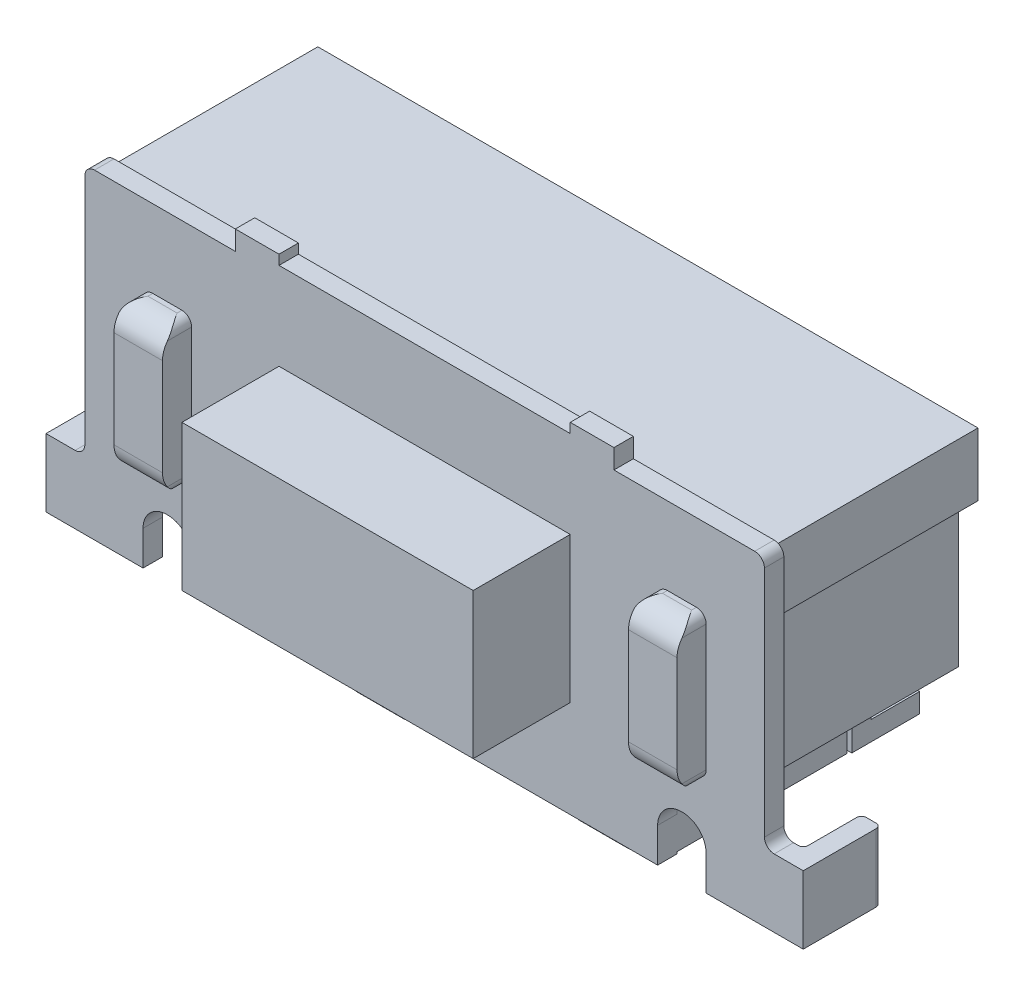
SolidWorks part; units mm, degrees
ref_plane "Alzado" through (0, 0, 0) normal (0, 0, 1) x (1, 0, 0)
ref_plane "Planta" through (0, 0, 0) normal (0, 1, 0) x (1, 0, 0)
ref_plane "Vista lateral" through (0, 0, 0) normal (1, 0, 0) x (0, 0, -1)
sketch "Croquis2" plane through (0, 0, 0) normal (0, 0, 1) x (1, 0, 0)
  line L0 (0, 0) -> (7.8, 0)
  line L1 (7.8, 0) -> (7.8, 3.5)
  line L2 (7.8, 3.5) -> (0, 3.5)
  line L3 (0, 3.5) -> (0, 0)
  dimension "D1" = 3.5
  dimension "D2" = 7.8
extrude "Saliente-Extruir1" add sketch "Croquis2" along normal blind 2.5
sketch "Croquis3" plane through (0, 0, 2.5) normal (0, 0, 1) x (1, 0, 0)
  line L0 (2.4, 2.5) -> (5.4, 2.5)
  line L5 (5.4, 1) -> (2.4, 1)
  line L6 (5.4, 2.5) -> (5.4, 1)
  line L8 (2.4, 1) -> (2.4, 2.5)
  dimension "D1" = 3
  dimension "D3" = 1.5
extrude "Saliente-Extruir2" add sketch "Croquis3" along normal blind 1
sketch "Croquis4" plane through (0, 0, 0) normal (0, -1, 0) x (1, 0, 0)
  line L0 (3.9, 2.5) -> (3.9, 1.5) construction
  line L1 (2.4, 2.5) -> (5.4, 2.5) construction
  line L6 (2.75, 1.5) -> (5.05, 1.5) construction
  circle A0 centre (5.05, 1.5) radius 0.4
  circle A1 centre (2.75, 1.5) radius 0.4
  dimension "D3" = 0.8
  dimension "D5" = 0.8
  dimension "D1" = 1
  dimension "D2" = 1.15
  dimension "D4" = 1.15
  dimension "D6" = 2.3
extrude "Saliente-Extruir3" add sketch "Croquis4" along normal blind 0.75
sketch "Croquis5" plane through (0, 0, 2.5) normal (0, 0, 1) x (1, 0, 0)
  line L0 (3.9, 3.5) -> (0.4, 3.5) construction
  line L1 (7.8, 3.5) -> (0, 3.5) construction
  line L2 (0.4, 3.5) -> (7.4, 3.5) construction
  line L3 (0.4, 0) -> (0.4, 0.7) construction
  line L4 (0, 0) -> (7.8, 0) construction
  line L5 (7.4, 0) -> (7.4, 0.7) construction
  line L9 (7.4, 3.5) -> (7.4, 0.7)
  line L10 (7.4, 0.7) -> (7.8, 0.7)
  line L11 (7.8, 0) -> (7.8, 3.5) construction
  line L12 (7.8, 0.7) -> (7.8, 3.5)
  line L13 (7.8, 3.5) -> (7.4, 3.5)
  line L16 (0.4, 3.5) -> (0.4, 0.7)
  line L17 (0.4, 0.7) -> (0, 0.7)
  line L18 (0, 3.5) -> (0, 0) construction
  line L19 (0, 0.7) -> (0, 3.5)
  line L20 (0, 3.5) -> (0.4, 3.5)
  dimension "D1" = 3.5
  dimension "D2" = 7
  dimension "D3" = 0.7
extrude "Cortar-Extruir1" cut sketch "Croquis5" against normal blind 2.5
sketch "Croquis6" plane through (0, 0, 2.5) normal (0, 0, 1) x (1, 0, 0)
  line L0 (0.2, 0.7) -> (0.3, 0.7)
  line L1 (0, 0.7) -> (0.4, 0.7) construction
  line L2 (0.4, 0.8) -> (0.4, 0.9)
  line L3 (0.4, 0.7) -> (0.4, 3.5) construction
  line L4 (0.2, 0.7) -> (0.4, 0.7)
  line L5 (0.4, 0.7) -> (0.4, 0.9)
  arc A0 (0.4, 0.8) -> (0.3, 0.7) centre (0.3, 0.8) cw
  point P10 (0.4, 0.7)
  line M3 (0.4, 3.5) -> (0.4, 0.7)
  line M4 (0.4, 0.7) -> (0, 0.7)
  dimension "D3" = 0.1
  dimension "D1" = 0.2
  dimension "D2" = 0.2
extrude "Saliente-Extruir4" add sketch "Croquis6" against normal blind 2.5 contours A0 M3 M4
sketch "Croquis7" plane through (0, 0, 2.5) normal (0, 0, 1) x (1, 0, 0)
  line L0 (7.6, 0.7) -> (7.5, 0.7)
  line L1 (7.4, 0.7) -> (7.8, 0.7) construction
  line L2 (7.4, 0.8) -> (7.4, 0.9)
  line L3 (7.4, 3.5) -> (7.4, 0.7) construction
  line L4 (7.4, 0.9) -> (7.4, 0.7)
  line L5 (7.4, 0.7) -> (7.6, 0.7)
  arc A0 (7.5, 0.7) -> (7.4, 0.8) centre (7.5, 0.8) cw
  point P10 (7.4, 0.7)
  line M12 (7.8, 0.7) -> (7.4, 0.7)
  line M13 (7.4, 0.7) -> (7.4, 3.5)
  dimension "D2" = 0.1
  dimension "D1" = 0.2
extrude "Saliente-Extruir5" add sketch "Croquis7" against normal blind 2.5 contours A0 M12 M13
sketch "Croquis8" plane through (0, 0, 2.5) normal (0, 0, 1) x (1, 0, 0)
  line L0 (7.8, 0) -> (7.8, 3.5) construction
  line L1 (3.9, 0) -> (6.3, 0) construction
  line L2 (0, 0) -> (7.8, 0) construction
  line L3 (6.3, 0) -> (6.3, 1) construction
  line L4 (6.3, 1.1) -> (6.3, 2.4)
  line L5 (6.4, 2.5) -> (6.7, 2.5)
  line L6 (6.4, 1) -> (6.7, 1)
  line L7 (6.8, 1.1) -> (6.8, 2.4)
  line L8 (3.9, 0) -> (1.5, 0) construction
  line L9 (1.5, 0) -> (1.5, 1) construction
  line L10 (1.5, 1.1) -> (1.5, 2.4)
  line L11 (1.4, 2.5) -> (1.1, 2.5)
  line L12 (1, 2.4) -> (1, 1.1)
  line L13 (1.1, 1) -> (1.4, 1)
  arc A0 (6.7, 1) -> (6.8, 1.1) centre (6.7, 1.1) ccw
  arc A1 (6.4, 1) -> (6.3, 1.1) centre (6.4, 1.1) cw
  arc A2 (6.3, 2.4) -> (6.4, 2.5) centre (6.4, 2.4) cw
  arc A3 (6.7, 2.5) -> (6.8, 2.4) centre (6.7, 2.4) cw
  arc A4 (1.4, 1) -> (1.5, 1.1) centre (1.4, 1.1) ccw
  arc A5 (1.5, 2.4) -> (1.4, 2.5) centre (1.4, 2.4) ccw
  arc A6 (1.1, 2.5) -> (1, 2.4) centre (1.1, 2.4) ccw
  arc A7 (1, 1.1) -> (1.1, 1) centre (1.1, 1.1) ccw
  point P23 (6.3, 2.5)
  point P26 (6.8, 2.5)
  point P32 (1.5, 2.5)
  point P35 (1, 2.5)
  dimension "D5" = 0.1
  dimension "D6" = 0.1
  dimension "D7" = 0.1
  dimension "D8" = 0.1
  dimension "D9" = 0.1
  dimension "D10" = 0.1
  dimension "D11" = 0.1
  dimension "D12" = 0.1
  dimension "D1" = 2.4
  dimension "D2" = 0.5
  dimension "D3" = 2.4
  dimension "D4" = 0.5
extrude "Saliente-Extruir6" add sketch "Croquis8" along normal blind 0.3
sketch "Croquis9" plane through (0, 0, 2.5) normal (0, 0, 1) x (1, 0, 0)
  line L2 (3.9, 3.4) -> (5.4, 3.4)
  line L5 (7.4, 3.5) -> (0.4, 3.5) construction
  line L6 (2.4, 3.5) -> (2.4, 3.4)
  line L7 (5.4, 3.4) -> (5.4, 3.5)
  line L10 (2.4, 3.5) -> (1.95, 3.5)
  line L11 (1.95, 3.5) -> (1.95, 3.3)
  line L12 (1.95, 3.3) -> (0.5, 3.3)
  line L13 (1.95, 3.5) -> (0.4, 3.5)
  line L14 (0.4, 3.5) -> (0.4, 3.2)
  line L15 (2.4, 3.4) -> (3.9, 3.4)
  line L16 (5.4, 3.5) -> (5.85, 3.5)
  line L17 (5.85, 3.5) -> (5.85, 3.3)
  line L18 (5.85, 3.3) -> (7.3, 3.3)
  line L19 (7.4, 3.5) -> (7.4, 0.8) construction
  line L20 (7.4, 3.2) -> (7.4, 2.15)
  line L21 (2.4, 3.5) -> (5.4, 3.5)
  line L22 (5.85, 3.5) -> (7.4, 3.5)
  line L23 (7.4, 3.5) -> (7.4, 3.2)
  arc A0 (0.5, 3.3) -> (0.4, 3.2) centre (0.5, 3.2) ccw
  arc A1 (7.3, 3.3) -> (7.4, 3.2) centre (7.3, 3.2) cw
  point P18 (7.4, 3.3)
  line M15 (7.4, 0.8) -> (7.4, 3.5)
  line M16 (7.4, 3.5) -> (0.4, 3.5)
  line M17 (0.4, 3.5) -> (0.4, 0.8)
  dimension "D3" = 0.1
  dimension "D8" = 0.1
  dimension "D1" = 0.1
  dimension "D2" = 0.2
  dimension "D4" = 1.5
  dimension "D5" = 1.5
  dimension "D6" = 0.45
  dimension "D7" = 0.45
extrude "Cortar-Extruir2" cut sketch "Croquis9" against normal blind 2.5 contours A0 L12 L11 M16 M17 | L6 L15 L2 L7 M16 | L18 A1 L17 M15 M16
sketch "Croquis10" plane through (0, 0, 0) normal (0, -1, 0) x (1, 0, 0)
  line L0 (3.9, 2.5) -> (3.9, 2.3) construction
  line L1 (0, 2.5) -> (7.8, 2.5) construction
  line L2 (0.2, 2.25) -> (0.2, 1.75)
  line L4 (0.15, 1.7) -> (0.05, 1.7)
  line L5 (7.8, 2.5) -> (7.8, 0) construction
  line L6 (0.25, 2.3) -> (7.55, 2.3)
  line L7 (7.8, 2.45) -> (7.8, 1.75)
  line L8 (7.6, 2.25) -> (7.6, 1.75)
  line L9 (7.65, 1.7) -> (7.75, 1.7)
  line L10 (0, 2.5) -> (0, 0) construction
  line L11 (0, 1.75) -> (0, 2.45)
  line L12 (0.05, 2.5) -> (7.75, 2.5)
  line L13 (7.8, 1.75) -> (7.8, 0)
  line L14 (7.8, 0) -> (0, 0)
  line L15 (0, 0) -> (0, 1.75)
  arc A0 (0, 2.45) -> (0.05, 2.5) centre (0.05, 2.45) cw
  arc A1 (0.25, 2.3) -> (0.2, 2.25) centre (0.25, 2.25) ccw
  arc A2 (0.05, 1.7) -> (0, 1.75) centre (0.05, 1.75) cw
  arc A3 (0.2, 1.75) -> (0.15, 1.7) centre (0.15, 1.75) cw
  arc A4 (7.55, 2.3) -> (7.6, 2.25) centre (7.55, 2.25) cw
  arc A5 (7.8, 2.45) -> (7.75, 2.5) centre (7.75, 2.45) ccw
  arc A6 (7.8, 1.75) -> (7.75, 1.7) centre (7.75, 1.75) cw
  arc A7 (7.6, 1.75) -> (7.65, 1.7) centre (7.65, 1.75) ccw
  point P21 (0, 2.5)
  point P27 (0, 1.7)
  point P34 (7.8, 2.5)
  point P37 (7.8, 1.7)
  circle M20 centre (2.75, 1.5) radius 0.4
  circle M21 centre (5.05, 1.5) radius 0.4
  line M22 (0, 0) -> (7.8, 0)
  line M23 (7.8, 0) -> (7.8, 2.5)
  line M25 (0, 2.5) -> (0, 0)
  dimension "D2" = 0.05
  dimension "D3" = 0.05
  dimension "D5" = 0.05
  dimension "D6" = 0.05
  dimension "D7" = 0.05
  dimension "D8" = 0.05
  dimension "D9" = 0.05
  dimension "D10" = 0.05
  dimension "D1" = 0.2
  dimension "D4" = 0.8
extrude "Cortar-Extruir3" cut sketch "Croquis10" against normal blind 0.02 contours A7 L8 A4 L6 A1 L2 A3 L4 A2 A6 L9 M25 M22 M23 M21 M20
sketch "Croquis12" plane through (0, 3.3, 0) normal (0, 1, 0) x (1, 0, 0)
  line L0 (7.3, -2.5) -> (7.75, -2.5)
  line L1 (7.8, -2.45) -> (7.8, -1.75)
  line L2 (7.8, 0) -> (7.8, -2.5) construction
  line L3 (7.3, -2.5) -> (7.3, -2.3)
  line L4 (7.3, 0) -> (7.3, -2.5) construction
  line L5 (7.75, -1.7) -> (7.65, -1.7)
  line L6 (7.6, -1.75) -> (7.6, -2.25)
  line L7 (7.55, -2.3) -> (7.3, -2.3)
  line L8 (7.3, -2.3) -> (7.3, 0)
  line L9 (7.3, 0) -> (7.8, 0)
  line L10 (7.8, 0) -> (7.8, -1.75)
  line L11 (0.5, -2.5) -> (0.5, -2.3)
  line L12 (0.5, 0) -> (0.5, -2.5) construction
  line L13 (0.5, -2.5) -> (0.05, -2.5)
  line L14 (0, 0) -> (0, -2.5) construction
  line L15 (0, -2.45) -> (0, -1.75)
  line L16 (0.5, -2.3) -> (0.25, -2.3)
  line L17 (0.2, -2.25) -> (0.2, -1.75)
  line L18 (0.15, -1.7) -> (0.05, -1.7)
  line L19 (0.5, -2.3) -> (0.5, 0)
  line L20 (0.5, 0) -> (0, 0)
  line L21 (0, 0) -> (0, -1.75)
  arc A0 (7.65, -1.7) -> (7.6, -1.75) centre (7.65, -1.75) ccw
  arc A1 (7.8, -1.75) -> (7.75, -1.7) centre (7.75, -1.75) ccw
  arc A2 (7.6, -2.25) -> (7.55, -2.3) centre (7.55, -2.25) cw
  arc A3 (7.75, -2.5) -> (7.8, -2.45) centre (7.75, -2.45) ccw
  arc A4 (0.25, -2.3) -> (0.2, -2.25) centre (0.25, -2.25) cw
  arc A5 (0, -2.45) -> (0.05, -2.5) centre (0.05, -2.45) ccw
  arc A6 (0, -1.75) -> (0.05, -1.7) centre (0.05, -1.75) cw
  arc A7 (0.2, -1.75) -> (0.15, -1.7) centre (0.15, -1.75) ccw
  point P15 (7.6, -1.7)
  point P19 (7.8, -1.7)
  point P24 (7.8, -2.5)
  point P46 (0, -2.5)
  point P49 (0, -1.7)
  line M5 (7.3, -2.5) -> (7.3, 0)
  dimension "D4" = 0.05
  dimension "D5" = 0.05
  dimension "D6" = 0.05
  dimension "D7" = 0.05
  dimension "D8" = 0.05
  dimension "D9" = 0.05
  dimension "D11" = 0.05
  dimension "D12" = 0.05
  dimension "D1" = 0.2
  dimension "D2" = 0.8
  dimension "D3" = 0.2
  dimension "D10" = 0.8
extrude "Cortar-Extruir4" cut sketch "Croquis12" against normal blind 3.3 contours A2 L6 A0 L5 A1 L10 L9 L7 M5 | A7 L17 A4 L16 L19 L20 L21 A6 L18
sketch "Croquis13" plane through (0, 3.5, 0) normal (0, 1, 0) x (1, 0, 0)
  line L0 (0.5, -2.5) -> (0.5, -2.3)
  line L1 (0.5, -2.3) -> (7.3, -2.3)
  line L2 (7.3, -2.3) -> (7.3, -2.5)
  line L3 (7.3, -2.5) -> (0.5, -2.5)
  line L4 (7.3, -2.3) -> (7.3, 0)
  line L5 (7.3, 0) -> (0.5, 0)
  line L6 (0.5, 0) -> (0.5, -2.3)
  line M1 (5.85, 0) -> (5.4, 0)
  line M2 (5.4, 0) -> (5.4, -2.5)
  line M4 (5.85, -2.5) -> (5.85, 0)
extrude "Cortar-Extruir5" cut sketch "Croquis13" against normal blind 0.25 contours L5 L6 L1 M2 | L4 L5 L1 M4 | L1 M2 M4 M1
sketch "Croquis17" plane through (0, 0.02, 0) normal (0, -1, 0) x (1, 0, 0)
  line L0 (3.9, 0) -> (3.9, -0.5889) construction
  line L2 (3.9, 0) -> (6, 0) construction
  line L3 (0.5, 0) -> (7.3, 0) construction
  line L4 (3.9, 0) -> (2.1, 0) construction
  line L5 (6, 0) -> (6.3, 0) construction
  line L6 (6.3, -0.2) -> (6.3, 0.5)
  line L7 (3.9, 2.5) -> (3.9, -0.2) construction
  line L8 (0, 2.5) -> (7.8, 2.5) construction
  line L9 (3.9, -0.2) -> (6.3, -0.2) construction
  line L10 (6.3, 0.5) -> (5.7, 0.5)
  line L11 (5.7, 0.5) -> (5.7, -0.2)
  line L12 (5.7, -0.2) -> (6.3, -0.2)
  line L13 (3.9, -0.5889) -> (1.8, -0.5889) construction
  line L14 (2.1, -0.2) -> (1.5, -0.2)
  line L15 (1.5, -0.2) -> (1.5, 0.5)
  line L16 (1.5, 0.5) -> (2.1, 0.5)
  line L17 (2.1, 0.5) -> (2.1, -0.2)
  point P18 (1.8, 0)
  dimension "D1" = 2.1
  dimension "D2" = 2.1
  dimension "D3" = 0.3
  dimension "D4" = 2.7
  dimension "D5" = 0.7
  dimension "D6" = 0.6
  dimension "D7" = 0.6
  dimension "D8" = 0.7
extrude "Saliente-Extruir7" add sketch "Croquis17" along normal blind 0.02
sketch "Croquis18" plane through (0, 0.02, 0) normal (0, 1, 0) x (1, 0, 0)
  line L0 (1.5, 0.2) -> (2.1, 0.2)
  line L1 (2.1, 0.2) -> (2.1, 0)
  line L2 (2.1, 0) -> (1.5, 0)
  line L3 (1.5, 0) -> (1.5, 0.2)
  line L4 (5.7, 0.2) -> (6.3, 0.2)
  line L5 (6.3, 0.2) -> (6.3, 0)
  line L6 (6.3, 0) -> (5.7, 0)
  line L7 (5.7, 0) -> (5.7, 0.2)
extrude "Saliente-Extruir8" add sketch "Croquis18" along normal blind 0.8
sketch "Croquis19" plane through (0, 0, -0.2) normal (0, 0, -1) x (-1, 0, 0)
  line L0 (-6.3, 0) -> (-5.7, 0)
  line L1 (-1.5, 0) -> (-1.5, 0.2)
  line L2 (-5.7, 0.82) -> (-5.7, 0.02) construction
  line L3 (-5.7, 0.2) -> (-6.3, 0.2)
  line L4 (-6.3, 0.82) -> (-6.3, 0.02) construction
  line L5 (-6.3, 0.2) -> (-6.3, 0.82)
  line L6 (-5.7, 0.2) -> (-5.7, 0.82)
  line L7 (-5.7, 0.82) -> (-6.3, 0.82) construction
  line L8 (-6.3, 0.82) -> (-5.7, 0.82) construction
  line L9 (-5.7, 0.82) -> (-6.3, 0.82)
  line L10 (-1.5, 0) -> (-1.5, 0.82) construction
  line L11 (-1.5, 0.2) -> (-2.1, 0.2)
  line L12 (-2.1, 0.82) -> (-2.1, 0.02) construction
  line L13 (-2.1, 0.2) -> (-2.1, 0.82)
  line L14 (-2.1, 0.82) -> (-1.5, 0.82)
  line L15 (-1.5, 0.82) -> (-1.5, 0.2)
  line M3 (-5.7, 0) -> (-5.7, 0.82)
  line M4 (-5.7, 0.82) -> (-6.3, 0.82)
  line M5 (-6.3, 0.82) -> (-6.3, 0)
  dimension "D1" = 0.2
  dimension "D2" = 0.2
extrude "Cortar-Extruir8" cut sketch "Croquis19" against normal blind 0.5 contours L3 M3 M4 M5 | L15 L14 L13 L11
sketch "Croquis20" plane through (0, 0, 0) normal (0, -1, 0) x (1, 0, 0)
  line L0 (1.5, 0.5) -> (2.1, 0.5)
  line L1 (2.1, 0.5) -> (2.1, 0.55)
  line L2 (2.1, 0.55) -> (1.5, 0.55)
  line L3 (1.5, 0.55) -> (1.5, 0.5)
  line L4 (5.7, 0.5) -> (5.7, 0.55)
  line L5 (5.7, 0.55) -> (6.3, 0.55)
  line L6 (6.3, 0.55) -> (6.3, 0.5)
  line L7 (6.3, 0.5) -> (5.7, 0.5)
  dimension "D1" = 0.05
extrude "Cortar-Extruir9" cut sketch "Croquis20" against normal blind 0.8 contours L3 L0 L1 L2 | L7 L4 L5 L6
sketch "Croquis21" plane through (0, 0.02, 0) normal (0, -1, 0) x (1, 0, 0)
  line L0 (1.5, 0) -> (0.9, 0)
  line L1 (0.5, 0) -> (1.5, 0) construction
  line L2 (1.5, 0) -> (1.5, 2.3)
  line L3 (0.5, 2.3) -> (7.3, 2.3) construction
  line L4 (0.9, 0) -> (0.9, 2.3)
  line L5 (0.25, 2.3) -> (7.55, 2.3) construction
  line L6 (0.9, 2.3) -> (1.5, 2.3)
  line L7 (6.3, 0) -> (6.9, 0)
  line L8 (6.3, 0) -> (7.3, 0) construction
  line L9 (6.3, 0) -> (6.3, 2.3)
  line L10 (6.3, 2.3) -> (6.9, 2.3)
  line L11 (6.9, 2.3) -> (6.9, 0)
  dimension "D1" = 0.6
  dimension "D2" = 0.6
extrude "Cortar-Extruir10" cut sketch "Croquis21" against normal blind 0.8
sketch "Croquis22" plane through (0, 0.02, 0) normal (0, -1, 0) x (1, 0, 0)
  line L0 (0.9, 0) -> (0.9, 2.3)
  line L1 (0.9, 2.3) -> (0.5, 2.3)
  line L2 (0.5, 2.3) -> (0.5, 0)
  line L3 (0.5, 0) -> (0.9, 0)
  line L4 (6.9, 2.3) -> (7.3, 2.3)
  line L5 (7.3, 2.3) -> (7.3, 0)
  line L6 (7.3, 0) -> (6.9, 0)
  line L7 (6.9, 0) -> (6.9, 2.3)
extrude "Cortar-Extruir11" cut sketch "Croquis22" against normal blind 2.58
sketch "Croquis23" plane through (0, 0.02, 0) normal (0, -1, 0) x (1, 0, 0)
  line L0 (2.1, 0) -> (2.1, 0.55)
  line L1 (2.1, 0.55) -> (5.7, 0.55)
  line L2 (5.7, 0.55) -> (5.7, 0)
  line L3 (5.7, 0) -> (2.1, 0)
extrude "Cortar-Extruir12" cut sketch "Croquis23" against normal blind 0.8
sketch "Croquis24" plane through (0, 0, 0) normal (0, 0, -1) x (-1, 0, 0)
  line L0 (-7.3, 2.6) -> (-7.3, 3.25)
  line L1 (-7.3, 3.25) -> (-0.5, 3.25)
  line L2 (-0.5, 3.25) -> (-0.5, 2.6)
  line L3 (-0.5, 2.6) -> (-7.3, 2.6)
extrude "Cortar-Extruir13" cut sketch "Croquis24" against normal blind 0.2
sketch "Croquis25" plane through (6.8, 0, 0) normal (1, 0, 0) x (0, 0, -1)
  line L0 (-2.5, 1) -> (-2.55, 1)
  line L1 (-3.5, 1) -> (-2.5, 1) construction
  line L2 (-2.8, 1) -> (-2.5, 1) construction
  line L3 (-2.8, 1.25) -> (-2.8, 2.25)
  line L4 (-2.55, 2.5) -> (-2.5, 2.5)
  line L5 (-2.5, 2.5) -> (-2.5, 1)
  line L6 (-2.5, 2.5) -> (-2.8, 2.5)
  line L7 (-2.8, 2.5) -> (-2.8, 2.25)
  line L8 (-2.5, 1) -> (-2.8, 1)
  line L9 (-2.8, 1) -> (-2.8, 1.25)
  arc A0 (-2.55, 1) -> (-2.8, 1.25) centre (-2.55, 1.25) cw
  arc A1 (-2.8, 2.25) -> (-2.55, 2.5) centre (-2.55, 2.25) cw
  point P13 (-2.8, 1)
  point P16 (-2.8, 2.5)
  line M8 (-2.5, 2.4) -> (-2.8, 2.4)
  line M9 (-2.8, 2.4) -> (-2.8, 1.1)
  line M10 (-2.8, 1.1) -> (-2.5, 1.1)
  dimension "D1" = 0.25
  dimension "D2" = 0.25
extrude "Cortar-Extruir14" cut sketch "Croquis25" against normal blind 0.5 contours A1 L6 L7 M8 | A1 M9 M8 | L8 A0 L9 M10 | A0 M10 M9
sketch "Croquis26" plane through (1, 0, 0) normal (-1, 0, 0) x (0, 0, 1)
  line L0 (2.5, 2.5) -> (2.5, 1)
  line L1 (2.5, 1) -> (2.55, 1)
  line L2 (2.8, 1.25) -> (2.8, 2.25)
  line L3 (2.55, 2.5) -> (2.5, 2.5)
  line L4 (2.5, 2.5) -> (2.8, 2.5)
  line L5 (2.8, 2.5) -> (2.8, 2.25)
  line L6 (2.8, 1.25) -> (2.8, 1)
  line L7 (2.8, 1) -> (2.5, 1)
  arc A0 (2.55, 1) -> (2.8, 1.25) centre (2.55, 1.25) ccw
  arc A1 (2.8, 2.25) -> (2.55, 2.5) centre (2.55, 2.25) ccw
  point P10 (2.8, 1)
  point P13 (2.8, 2.5)
  line M9 (2.5, 1.1) -> (2.8, 1.1)
  line M10 (2.8, 1.1) -> (2.8, 2.4)
  line M11 (2.8, 2.4) -> (2.5, 2.4)
  dimension "D1" = 0.25
  dimension "D2" = 0.25
extrude "Cortar-Extruir15" cut sketch "Croquis26" against normal blind 0.5 contours A1 L5 L4 M11 | A1 M10 M11 | A0 L7 L6 M9 | A0 M9 M10
sketch "Croquis28" plane through (0, 0, 2.5) normal (0, 0, 1) x (1, 0, 0)
  line L0 (1, 1.1) -> (1, 0) construction
  line L1 (0, 0) -> (7.8, 0) construction
  line L2 (1.5, 1.1) -> (1.5, 0) construction
  line L3 (6.8, 1.1) -> (6.8, 0) construction
  line L4 (6.3, 1.1) -> (6.3, 0) construction
  line L5 (1, 0) -> (1.5, 0)
  line L6 (6.3, 0) -> (6.8, 0)
  line L7 (6.3, 0) -> (6.3, 0.355)
  line L8 (6.545, 0.6) -> (6.555, 0.6)
  line L9 (6.8, 0.355) -> (6.8, 0)
  line L10 (1.5, 0) -> (1.5, 0.355)
  line L11 (1.255, 0.6) -> (1.245, 0.6)
  line L12 (1, 0.355) -> (1, 0)
  arc A0 (6.555, 0.6) -> (6.8, 0.355) centre (6.555, 0.355) cw
  arc A1 (6.3, 0.355) -> (6.545, 0.6) centre (6.545, 0.355) cw
  arc A2 (1.5, 0.355) -> (1.255, 0.6) centre (1.255, 0.355) ccw
  arc A3 (1.245, 0.6) -> (1, 0.355) centre (1.245, 0.355) ccw
  point P22 (6.8, 0.6)
  point P25 (6.3, 0.6)
  point P28 (1.5, 0.6)
  point P31 (1, 0.6)
  dimension "D3" = 0.245
  dimension "D4" = 0.245
  dimension "D5" = 0.245
  dimension "D6" = 0.245
  dimension "D1" = 0.5
  dimension "D2" = 0.6
extrude "Cortar-Extruir16" cut sketch "Croquis28" against normal blind 0.5
sketch "Croquis29" plane through (0, 0, 2.5) normal (0, 0, 1) x (1, 0, 0)
  line L0 (2.6, -0.75) -> (2.9, -0.75)
  line L1 (2.35, -0.75) -> (3.15, -0.75) construction
  line L2 (3.15, -0.5) -> (3.15, 0)
  line L3 (1.5, 0) -> (6.3, 0) construction
  line L4 (3.15, -0.75) -> (3.15, 0.02) construction
  line L5 (3.15, 0) -> (2.35, 0)
  line L6 (2.35, 0.02) -> (2.35, -0.75) construction
  line L7 (2.35, 0) -> (2.35, -0.5)
  line L8 (4.9, -0.75) -> (5.2, -0.75)
  line L9 (5.45, -0.5) -> (5.45, 0)
  line L10 (5.45, -0.75) -> (5.45, 0.02) construction
  line L11 (4.65, -0.5) -> (4.65, 0)
  line L12 (4.65, 0.02) -> (4.65, -0.75) construction
  line L13 (4.65, 0) -> (5.45, 0)
  line L14 (2.35, -0.5) -> (2.35, -0.75)
  line L15 (2.35, -0.75) -> (2.6, -0.75)
  line L16 (2.9, -0.75) -> (3.15, -0.75)
  line L17 (3.15, -0.75) -> (3.15, -0.5)
  line L18 (5.45, -0.5) -> (5.45, -0.75)
  line L19 (5.45, -0.75) -> (5.2, -0.75)
  line L20 (4.9, -0.75) -> (4.65, -0.75)
  line L21 (4.65, -0.75) -> (4.65, -0.5)
  arc A0 (5.2, -0.75) -> (5.45, -0.5) centre (5.2, -0.5) ccw
  arc A1 (4.9, -0.75) -> (4.65, -0.5) centre (4.9, -0.5) cw
  arc A2 (2.9, -0.75) -> (3.15, -0.5) centre (2.9, -0.5) ccw
  arc A3 (2.6, -0.75) -> (2.35, -0.5) centre (2.6, -0.5) cw
  point P27 (5.45, -0.75)
  point P30 (4.65, -0.75)
  point P33 (3.15, -0.75)
  point P36 (2.35, -0.75)
  dimension "D1" = 0.25
  dimension "D2" = 0.25
  dimension "D3" = 0.25
  dimension "D4" = 0.25
extrude "Cortar-Extruir17" cut sketch "Croquis29" against normal blind 1.4 contours L15 A3 L14 | A2 L16 L17 | L20 A1 L21 | A0 L19 L18
sketch "Croquis30" plane through (1.5, 0, 0) normal (-1, 0, 0) x (0, 0, 1)
  line L0 (1.1, 0.02) -> (1.9, 0.02)
  line L1 (1.1, 0.02) -> (1.9, 0.02) construction
  line L2 (0.55, 0.02) -> (2.3, 0.02) construction
  line L3 (1.9, 0.02) -> (1.9, -0.5)
  line L4 (1.65, -0.75) -> (1.35, -0.75)
  line L5 (1.1, -0.5) -> (1.1, 0.02)
  line L6 (1.1, -0.5) -> (1.1, -0.75)
  line L7 (1.1, -0.75) -> (1.35, -0.75)
  line L8 (1.9, -0.5) -> (1.9, -0.75)
  line L9 (1.9, -0.75) -> (1.65, -0.75)
  arc A0 (1.9, -0.5) -> (1.65, -0.75) centre (1.65, -0.5) cw
  arc A1 (1.35, -0.75) -> (1.1, -0.5) centre (1.35, -0.5) cw
  point P13 (1.9, -0.75)
  point P16 (1.1, -0.75)
  dimension "D1" = 0.25
  dimension "D2" = 0.25
extrude "Cortar-Extruir18" cut sketch "Croquis30" against normal blind 1.65 contours L7 A1 L6 | L8 A0 L9
sketch "Croquis31" plane through (6.3, 0, 0) normal (1, 0, 0) x (0, 0, -1)
  line L0 (-1.1, 0.02) -> (-1.1, -0.5)
  line L1 (-1.35, -0.75) -> (-1.65, -0.75)
  line L2 (-1.1, 0.02) -> (-1.9, 0.02)
  line L3 (-2.3, 0.02) -> (-0.55, 0.02) construction
  line L4 (-1.9, 0.02) -> (-1.1, 0.02) construction
  line L5 (-1.9, 0.02) -> (-1.9, -0.5)
  line L6 (-1.9, -0.5) -> (-1.9, -0.75)
  line L7 (-1.9, -0.75) -> (-1.65, -0.75)
  line L8 (-1.35, -0.75) -> (-1.1, -0.75)
  line L9 (-1.1, -0.75) -> (-1.1, -0.5)
  arc A0 (-1.1, -0.5) -> (-1.35, -0.75) centre (-1.35, -0.5) cw
  arc A1 (-1.65, -0.75) -> (-1.9, -0.5) centre (-1.65, -0.5) cw
  point P13 (-1.1, -0.75)
  point P16 (-1.9, -0.75)
  dimension "D1" = 0.25
  dimension "D2" = 0.25
extrude "Cortar-Extruir19" cut sketch "Croquis31" against normal blind 1.65 contours L7 A1 L6 | L9 A0 L8
